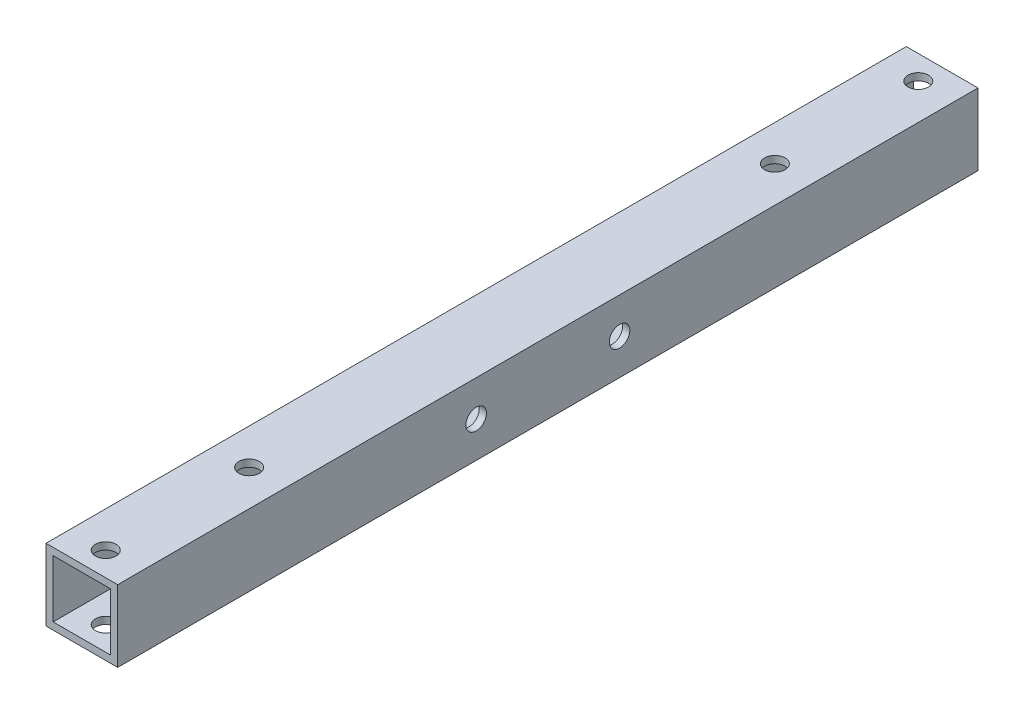
SolidWorks part; units mm, degrees
material "5052-H34"
ref_plane "正面" through (0, 0, 0) normal (0, 0, 1) x (1, 0, 0)
ref_plane "平面" through (0, 0, 0) normal (0, 1, 0) x (1, 0, 0)
ref_plane "右側面" through (0, 0, 0) normal (1, 0, 0) x (0, 0, -1)
sketch "ｽｹｯﾁ1" plane through (0, 0, 0) normal (0, 0, 1) x (1, 0, 0)
  line L1 (-7.5, 7.5) -> (7.5, 7.5)
  line L2 (-7.5, 7.5) -> (-7.5, -7.5)
  line L3 (-7.5, -7.5) -> (7.5, -7.5)
  line L4 (7.5, 7.5) -> (7.5, -7.5)
  line L5 (-7.5, 7.5) -> (7.5, -7.5) construction
  line L6 (-7.5, -7.5) -> (7.5, 7.5) construction
  point P0 (0, 0)
  dimension "D1" = 15
  dimension "D2" = 15
extrude "押し出し-薄板1" add sketch "ｽｹｯﾁ1" along normal blind 180 thin
sketch "ｽｹｯﾁ3" plane through (7.5, 0, 0) normal (1, 0, 0) x (0, 0, -1)
  line L0 (-90, 7.5) -> (-90, -7.5) construction
  line L1 (-180, 7.5) -> (0, 7.5) construction
  line L2 (-180, -7.5) -> (0, -7.5) construction
  line L3 (-90, 0) -> (-75, 0) construction
  circle A0 centre (-75, 0) radius 2.15
  circle A1 centre (-105, 0) radius 2.15
  dimension "D1" = 4.3
  dimension "D2" = 30
extrude "ｶｯﾄ - 押し出し2" cut sketch "ｽｹｯﾁ3" against normal through all
sketch "ｽｹｯﾁ4" plane through (0, 7.5, 0) normal (0, 1, 0) x (1, 0, 0)
  line L0 (-7.5, -90) -> (7.5, -90) construction
  line L1 (-7.5, -180) -> (-7.5, 0) construction
  line L2 (7.5, -180) -> (7.5, 0) construction
  line L3 (0, -90) -> (0, -35) construction
  line L4 (0, -35) -> (0, -5) construction
  circle A0 centre (0, -35) radius 2.15
  circle A1 centre (0, -145) radius 2.15
  circle A2 centre (0, -5) radius 2.15
  circle A3 centre (0, -175) radius 2.15
  circle A4 centre (0, -145) radius 2.15
  dimension "D1" = 4.3
  dimension "D2" = 30
  dimension "D3" = 5
extrude "ｶｯﾄ - 押し出し3" cut sketch "ｽｹｯﾁ4" against normal through all contours A2 | A0 | A3 | A1
